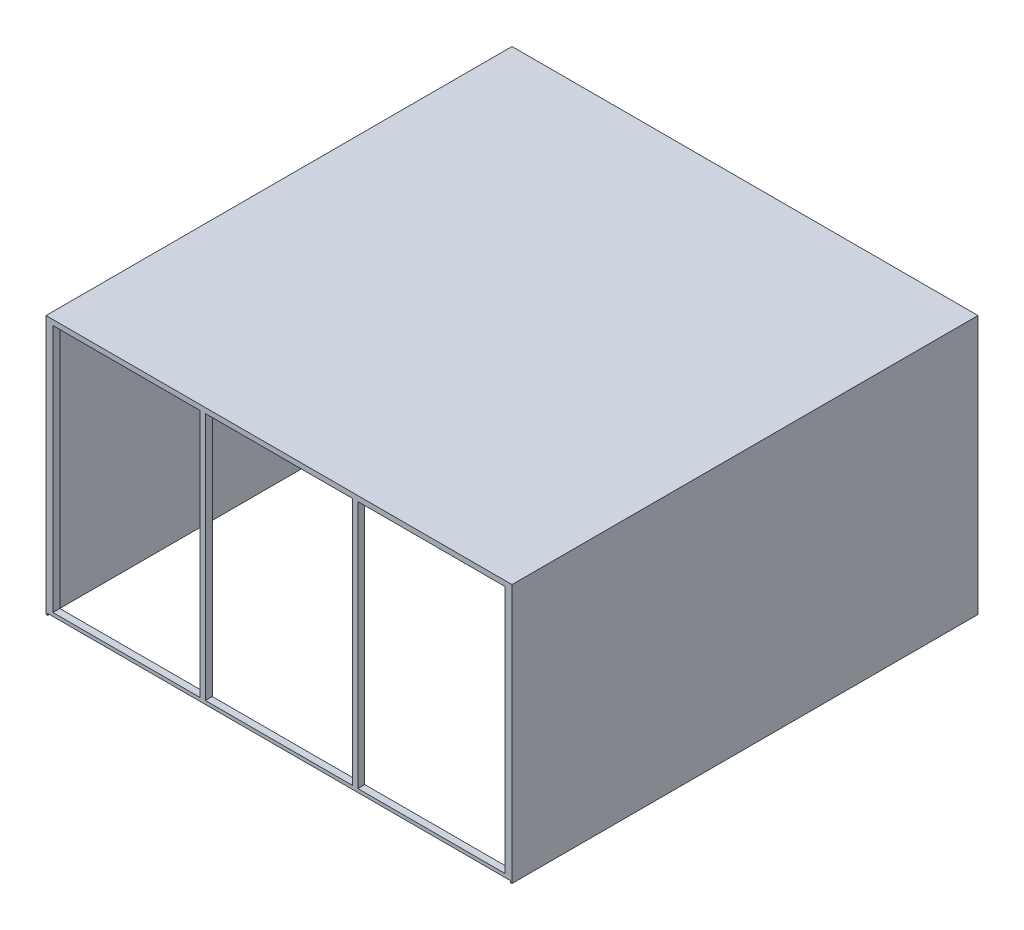
SolidWorks part; units mm, degrees
ref_plane "Front Plane" through (0, 0, 0) normal (0, 0, 1) x (1, 0, 0)
ref_plane "Top Plane" through (0, 0, 0) normal (0, 1, 0) x (1, 0, 0)
ref_plane "Right Plane" through (0, 0, 0) normal (1, 0, 0) x (0, 0, -1)
sketch "Sketch1" plane through (0, 0, 0) normal (0, 1, 0) x (1, 0, 0)
  line L0 (337.5, 0) -> (-337.5, 0)
  line L1 (-337.5, 0) -> (-337.5, 675)
  line L2 (-337.5, 675) -> (337.5, 675)
  line L3 (337.5, 675) -> (337.5, 0)
  point P4 (0, 0)
  dimension "D1" = 675
  dimension "D2" = 675
extrude "Boss-Extrude1" add sketch "Sketch1" along normal blind 375
sketch "Sketch4" plane through (0, 0, 0) normal (0, 0, 1) x (1, 0, 0)
  line L0 (0, 0) -> (0, 375) construction
  line L1 (-337.5, 0) -> (337.5, 0) construction
  line L2 (-337.5, 375) -> (337.5, 375) construction
  line L8 (335, 2.5) -> (-335, 2.5)
  line L9 (335, 2.5) -> (335, 372.5)
  line L10 (335, 372.5) -> (-335, 372.5)
  line L11 (-335, 2.5) -> (-335, 372.5)
  line L12 (335, 2.5) -> (-335, 372.5) construction
  line L13 (335, 372.5) -> (-335, 2.5) construction
  point P6 (0, 187.5)
  point P7 (0, 187.5)
  dimension "D1" = 370
  dimension "D2" = 670
extrude "Cut-Extrude3" cut sketch "Sketch4" against normal blind 662.5 from offset 10 offset against normal yes
sketch "Sketch6" plane through (0, 0, 0) normal (0, 0, 1) x (1, 0, 0)
  line L0 (0, 0) -> (0, 372.5) construction
  line L1 (335, 372.5) -> (-335, 372.5) construction
  line L2 (-335, 372.5) -> (-335, 2.5) construction
  line L3 (335, -2.5) -> (-335, -2.5)
  line L4 (335, -2.5) -> (335, 2.5)
  line L5 (335, 2.5) -> (-335, 2.5)
  line L6 (-335, -2.5) -> (-335, 2.5)
  line L7 (335, -2.5) -> (-335, 2.5) construction
  line L8 (335, 2.5) -> (-335, -2.5) construction
  point P11 (0, 0)
  dimension "D1" = 5
extrude "Cut-Extrude4" cut sketch "Sketch6" against normal blind 670
ref_plane "Plane2" through (-337.5, 375, 0) normal (0, -1, 0) x (-1, 0, 0)
sketch "Sketch7" plane through (-337.5, 375, 0) normal (0, -1, 0) x (1, 0, 0)
sketch "Sketch9" plane through (0, 0, 0) normal (0, 0, 1) x (1, 0, 0)
  line L0 (0, 0) -> (0, 375) construction
  line L1 (-337.5, 375) -> (337.5, 375) construction
  line L3 (320, 7.5) -> (-320, 7.5)
  line L4 (320, 7.5) -> (320, 367.5)
  line L5 (320, 367.5) -> (-320, 367.5)
  line L6 (-320, 7.5) -> (-320, 367.5)
  line L7 (320, 7.5) -> (-320, 367.5) construction
  line L8 (320, 367.5) -> (-320, 7.5) construction
  point P5 (0, 187.5)
  dimension "D1" = 360
  dimension "D2" = 640
sketch "Sketch11" plane through (0, 0, 0) normal (0, 0, 1) x (1, 0, 0)
  line L1 (106.67, 7.5) -> (-106.67, 7.5)
  line L3 (-106.67, 7.5) -> (-106.67, 367.5)
  line L7 (-106.67, 367.5) -> (106.67, 367.5)
  line L8 (320, 7.5) -> (-320, 7.5) construction
  line L9 (106.67, 367.5) -> (106.67, 7.5)
  line L10 (320, 367.5) -> (-320, 367.5) construction
  line L13 (-327.5, 7.5) -> (-114.17, 7.5) construction
  line L14 (-335, 2.5) -> (-320, 2.5) construction
  line L15 (335, 2.5) -> (-335, 2.5) construction
  line L16 (-327.5, 2.5) -> (-327.5, 7.5) construction
  line L17 (-327.5, 7.5) -> (-320, 7.5) construction
  line L18 (-106.67, 7.5) -> (-114.17, 7.5) construction
  line L19 (-114.17, 7.5) -> (-327.5, 7.5)
  line L20 (-327.5, 7.5) -> (-327.5, 367.5)
  line L21 (-327.5, 367.5) -> (-114.17, 367.5)
  line L22 (-114.17, 367.5) -> (-114.17, 7.5)
  line L23 (320, 7.5) -> (320, 2.5) construction
  line L24 (335, 2.5) -> (-335, 2.5) construction
  line L25 (320, 2.5) -> (335, 2.5) construction
  line L26 (327.5, 2.5) -> (327.5, 7.5) construction
  line L27 (320, 7.5) -> (327.5, 7.5) construction
  line L28 (327.5, 7.5) -> (114.17, 7.5)
  line L29 (114.17, 7.5) -> (114.17, 367.5)
  line L30 (114.17, 367.5) -> (327.5, 367.5)
  line L31 (327.5, 367.5) -> (327.5, 7.5)
  point P5 (-0.5972, 7.5)
  point P6 (36.009, 7.5)
  point P7 (-0.005, 7.5)
  point P12 (-106.67, 7.5)
  point P13 (0, 7.5)
  dimension "D1" = 213.33
  dimension "D2" = 213.33
  dimension "D3" = 7.5
extrude "Cut-Extrude6" cut sketch "Sketch11" against normal blind 10
